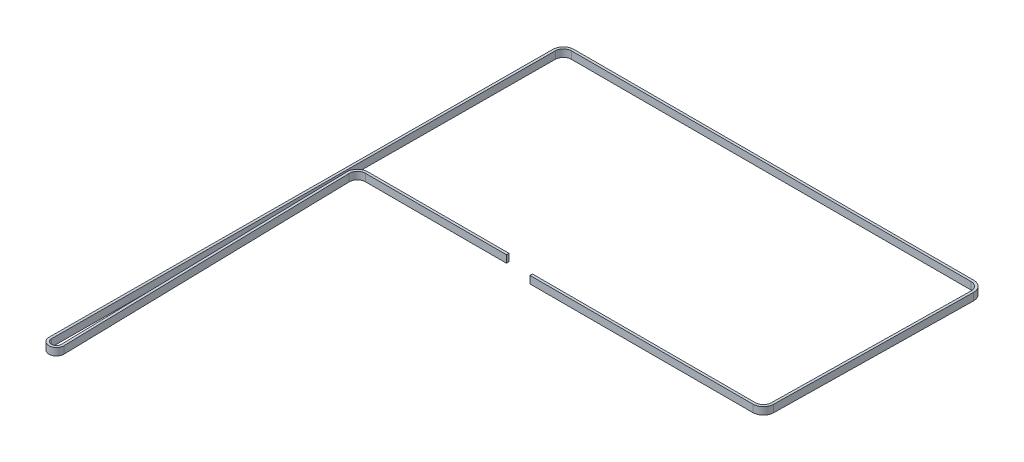
SolidWorks part; units mm, degrees
material "Rubber"
ref_plane "Front Plane" through (0, 0, 0) normal (0, 0, 1) x (1, 0, 0)
ref_plane "Top Plane" through (0, 0, 0) normal (0, 1, 0) x (1, 0, 0)
ref_plane "Right Plane" through (0, 0, 0) normal (1, 0, 0) x (0, 0, -1)
sketch "Sketch1" plane through (0, 506, 0) normal (0, -1, 0) x (1, 0, 0)
  line L0 (-159.5, -22.0774) -> (-45.1925, -22.0774) construction
  line L1 (-160.6515, 221.0144) -> (-165.9983, -15.4304) construction
  line L2 (-172.6499, 221.1182) -> (-170.4999, -185.045) construction
  line L3 (-162, -193.5) -> (162, -193.5) construction
  line L4 (170.499, -184.8667) -> (167.999, -25.4441) construction
  line L5 (159.5, -17.0774) -> (-21.1925, -17.0774) construction
  line L6 (-159.5, -22.0774) -> (-45.1925, -22.0774)
  line L7 (-160.6515, 221.0144) -> (-165.9983, -15.4304)
  line L8 (-172.6499, 221.1182) -> (-170.4999, -185.045)
  line L9 (-162, -193.5) -> (162, -193.5)
  line L10 (170.499, -184.8667) -> (167.999, -25.4441)
  line L11 (159.5, -17.0774) -> (-21.1925, -17.0774)
  arc A0 (-165.9983, -15.4304) -> (-159.5, -22.0774) centre (-159.5, -15.5774) ccw construction
  arc A1 (-160.6515, 221.0144) -> (-172.6499, 221.1182) centre (-166.65, 221.15) ccw construction
  arc A2 (-170.4999, -185.045) -> (-162, -193.5) centre (-162, -185) ccw construction
  arc A3 (162, -193.5) -> (170.499, -184.8667) centre (162, -185) ccw construction
  arc A4 (167.999, -25.4441) -> (159.5, -17.0774) centre (159.5, -25.5774) ccw construction
  arc A5 (-165.9983, -15.4304) -> (-159.5, -22.0774) centre (-159.5, -15.5774) ccw
  arc A6 (-160.6515, 221.0144) -> (-172.6499, 221.1182) centre (-166.65, 221.15) ccw
  arc A7 (-170.4999, -185.045) -> (-162, -193.5) centre (-162, -185) ccw
  arc A8 (162, -193.5) -> (170.499, -184.8667) centre (162, -185) ccw
  arc A9 (167.999, -25.4441) -> (159.5, -17.0774) centre (159.5, -25.5774) ccw
extrude "Extrude-Thin1" add sketch "Sketch1" along normal blind 6 thin
